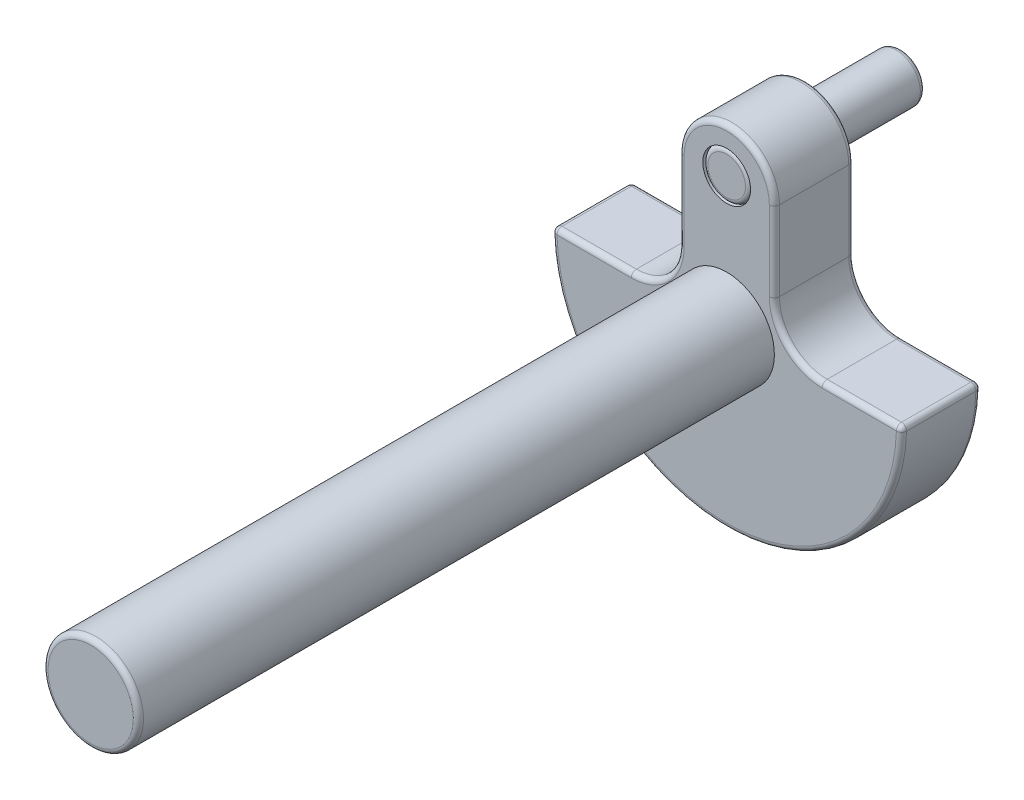
SolidWorks part; units mm, degrees
material "6061 Alloy"
ref_plane "Front Plane" through (0, 0, 0) normal (0, 0, 1) x (1, 0, 0)
ref_plane "Top Plane" through (0, 0, 0) normal (0, 1, 0) x (1, 0, 0)
ref_plane "Right Plane" through (0, 0, 0) normal (1, 0, 0) x (0, 0, -1)
sketch "Sketch1" plane through (0, 0, 0) normal (0, 0, 1) x (1, 0, 0)
  line L0 (-2.3813, 6.35) -> (-2.3813, 2.3813)
  line L1 (-4.7625, 0) -> (-8.7312, 0)
  line L2 (0, 6.35) -> (0, 0) construction
  line L3 (4.7625, 0) -> (8.7312, 0)
  line L4 (2.3812, 6.35) -> (2.3813, 2.3813)
  arc A0 (-8.7312, 0) -> (8.7312, 0) centre (0, 0) ccw
  arc A1 (2.3812, 6.35) -> (-2.3813, 6.35) centre (0, 6.35) ccw
  arc A2 (4.7625, 0) -> (2.3813, 2.3813) centre (4.7625, 2.3813) cw
  arc A3 (-2.3813, 2.3813) -> (-4.7625, 0) centre (-4.7625, 2.3812) cw
  point P11 (2.3813, 0)
  point P14 (-2.3812, 0)
  dimension "D1" = 8.7312
  dimension "D2" = 2.3813
  dimension "D4" = 2.3813
  dimension "D3" = 6.35
extrude "Boss-Extrude1" add sketch "Sketch1" along normal blind 3.9688 contours L0 A3 L1 A0 L3 A2 L4 A1
sketch "Sketch2" plane through (0, 0, 3.9688) normal (0, 0, 1) x (1, 0, 0)
  circle A0 centre (0, 0) radius 1.9844
  circle A1 centre (0, 6.5408) radius 1.1906
  dimension "D1" = 2.3813
  dimension "D2" = 3.9688
extrude "Cut-Extrude1" cut sketch "Sketch2" against normal through all
sketch "Sketch3" plane through (0, 0, 0) normal (0, 0, -1) x (-1, 0, 0)
  circle A0 centre (0, 6.5408) radius 1.1906
extrude "Boss-Extrude2" add sketch "Sketch3" along normal blind 4.7625 and the other way up to surface (3.9688 mm away) separate body contours A0 other way up to face at (1.9844, 0, 3.9688)
sketch "Sketch4" plane through (0, 0, 0) normal (1, 0, 0) x (0, 0, -1)
  line L0 (-3.9688, 0) -> (-35.7188, 0) construction
  line L1 (-35.7188, 0) -> (-35.7188, 2.3812)
  line L2 (-35.7188, 2.3812) -> (-3.9688, 2.3812)
  line L3 (-3.9688, 6.35) -> (-3.9688, 2.3813) construction
  line L4 (-3.9688, 2.3812) -> (-3.9688, 1.9844)
  line L5 (-3.9688, 1.9844) -> (0, 1.9844)
  line L6 (0, 1.9844) -> (0, 0)
  line L7 (0, 0) -> (-3.9688, 0)
  line L8 (-3.9688, 0) -> (-35.7188, 0)
  dimension "D1" = 4.7625
  dimension "D2" = 31.75
revolve "Revolve1" add sketch "Sketch4" angle 360 about L0
fillet "Fillet1" radius 0.254 20 edges at (6.7469, 0, 3.9688) (3.0787, 0.6975, 3.9688) (2.3813, 4.3656, 3.9688) (0, 8.7312, 3.9688) (-2.3813, 4.3656, 3.9688) (-3.0787, 0.6975, 3.9688) (6.7469, 0, 0) (3.0787, 0.6975, 0) (2.3813, 4.3656, 0) (0, 8.7312, 0) (-2.3813, 4.3656, 0) (-3.0787, 0.6975, 0) (0, -8.7312, 3.9688) (-6.7469, 0, 3.9688) (0, -8.7312, 0) (-6.7469, 0, 0) (1.9844, 0, 0) (1.1906, 6.5408, 0) (8.7312, 0, 1.9844) (-8.7312, 0, 1.9844)
fillet "Fillet2" radius 0.254 2 edges at (-1.1906, 6.5408, -4.7625) (1.1906, 6.5408, 3.9688)
fillet "Fillet3" radius 0.254 1 edges at (0, 2.3812, 35.7188)
